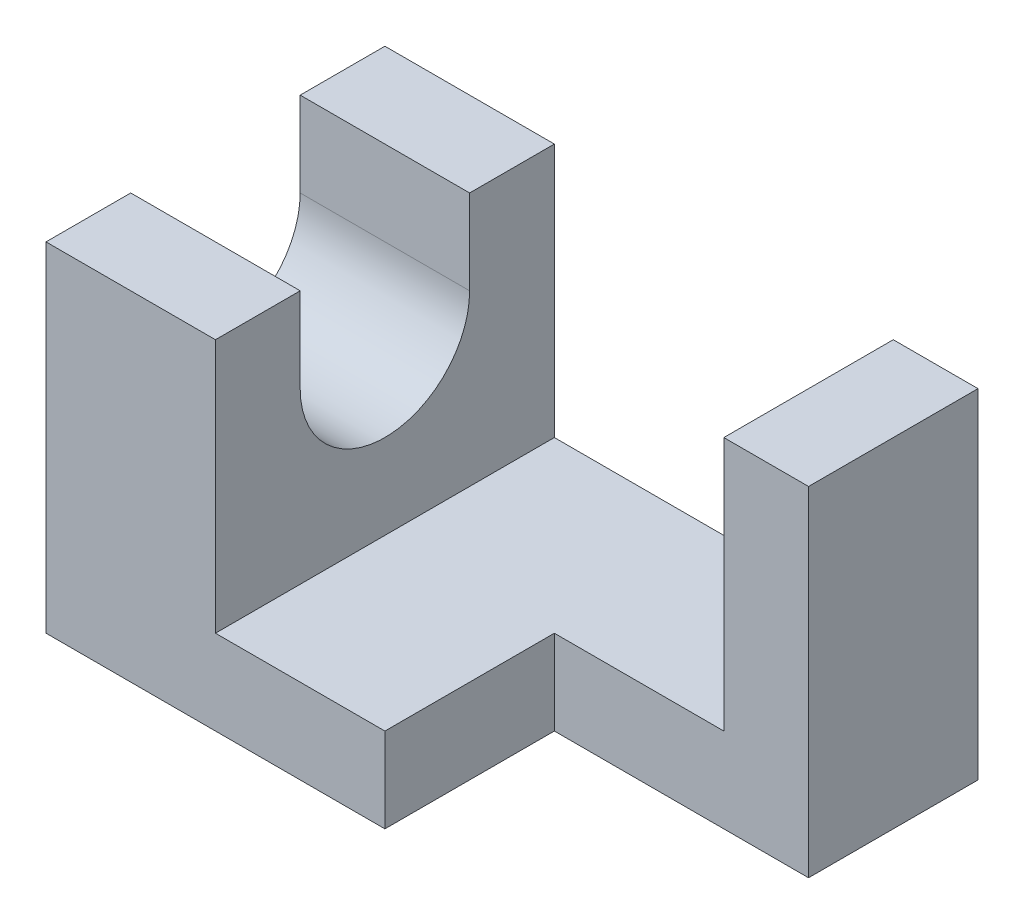
SolidWorks part; units mm, degrees
ref_plane "정면" through (0, 0, 0) normal (0, 0, 1) x (1, 0, 0)
ref_plane "윗면" through (0, 0, 0) normal (0, 1, 0) x (1, 0, 0)
ref_plane "우측면" through (0, 0, 0) normal (1, 0, 0) x (0, 0, -1)
sketch "스케치1" plane through (0, 0, 0) normal (0, 0, 1) x (1, 0, 0)
  line L1 (0, 0) -> (70, 0)
  line L2 (0, 0) -> (0, 40)
  line L3 (0, 40) -> (70, 40)
  line L4 (70, 0) -> (70, 40)
  dimension "D1" = 70
  dimension "D2" = 40
extrude "보스-돌출1" add sketch "스케치1" against normal blind 40
sketch "스케치2" plane through (0, 0, 0) normal (0, 0, 1) x (1, 0, 0)
  line L0 (70, 40) -> (0, 40) construction
  line L1 (20, 40) -> (60, 40)
  line L2 (20, 40) -> (20, 10)
  line L3 (20, 10) -> (60, 10)
  line L4 (60, 40) -> (60, 10)
  line L5 (70, 0) -> (70, 40) construction
  dimension "D1" = 30
  dimension "D2" = 40
  dimension "D3" = 10
extrude "컷-돌출1" cut sketch "스케치2" against normal blind 40
sketch "스케치3" plane through (0, 40, 0) normal (0, 1, 0) x (1, 0, 0)
  line L1 (70, 0) -> (40, 0)
  line L2 (70, 0) -> (70, 20)
  line L3 (70, 20) -> (40, 20)
  line L4 (40, 0) -> (40, 20)
  dimension "D1" = 30
  dimension "D2" = 20
extrude "컷-돌출2" cut sketch "스케치3" against normal blind 40
sketch "스케치4" plane through (0, 0, 0) normal (-1, 0, 0) x (0, 0, 1)
  line L0 (-30, 40) -> (-30, 30)
  line L1 (-40, 40) -> (0, 40) construction
  line L2 (-10, 30) -> (-10, 40)
  line L3 (-10, 40) -> (-30, 40)
  line L5 (-40, 40) -> (-40, 0) construction
  arc A0 (-30, 30) -> (-10, 30) centre (-20, 30) ccw
  dimension "D1" = 20
  dimension "D2" = 20
extrude "컷-돌출3" cut sketch "스케치4" against normal blind 40
